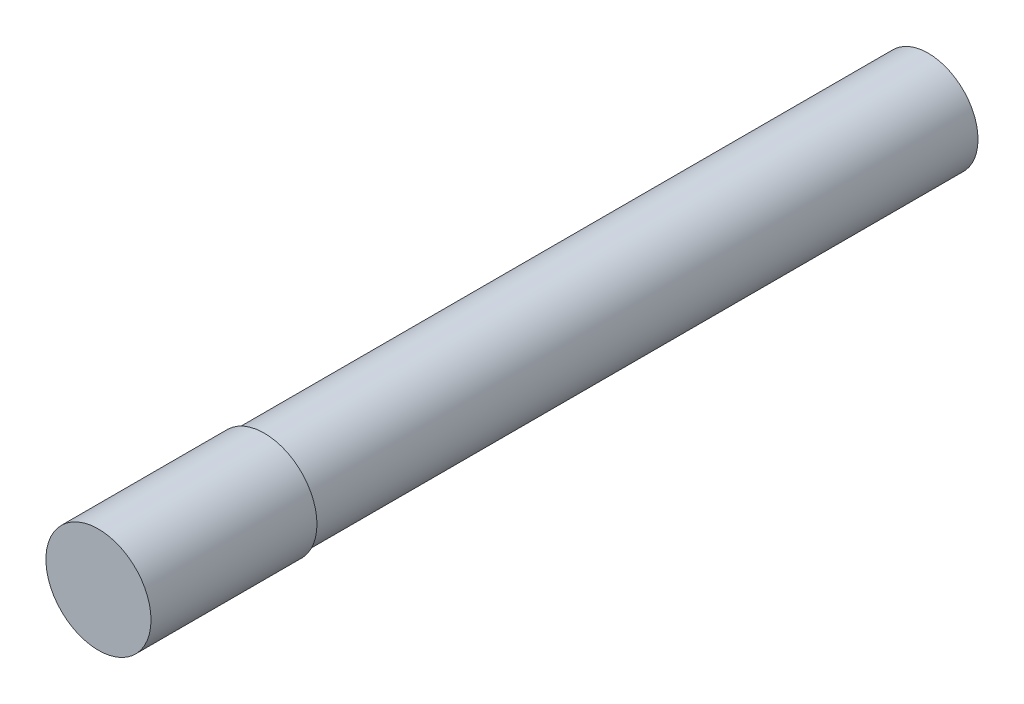
SolidWorks part; units mm, degrees
ref_plane "Front Plane" through (0, 0, 0) normal (0, 0, 1) x (1, 0, 0)
ref_plane "Top Plane" through (0, 0, 0) normal (0, 1, 0) x (1, 0, 0)
ref_plane "Right Plane" through (0, 0, 0) normal (1, 0, 0) x (0, 0, -1)
sketch "Sketch1" plane through (0, 0, 0) normal (0, 0, 1) x (1, 0, 0)
  circle A0 centre (0, 0) radius 9
extrude "Barrel" add sketch "Sketch1" along normal blind 120
ref_plane "P_Front_120" through (0, 0, 120) normal (0, 0, 1) x (1, 0, 0)
sketch "Sketch2" plane through (0, 0, 120) normal (0, 0, 1) x (1, 0, 0)
  circle A0 centre (0, 0) radius 9.5
extrude "Cap" add sketch "Sketch2" along normal blind 30
